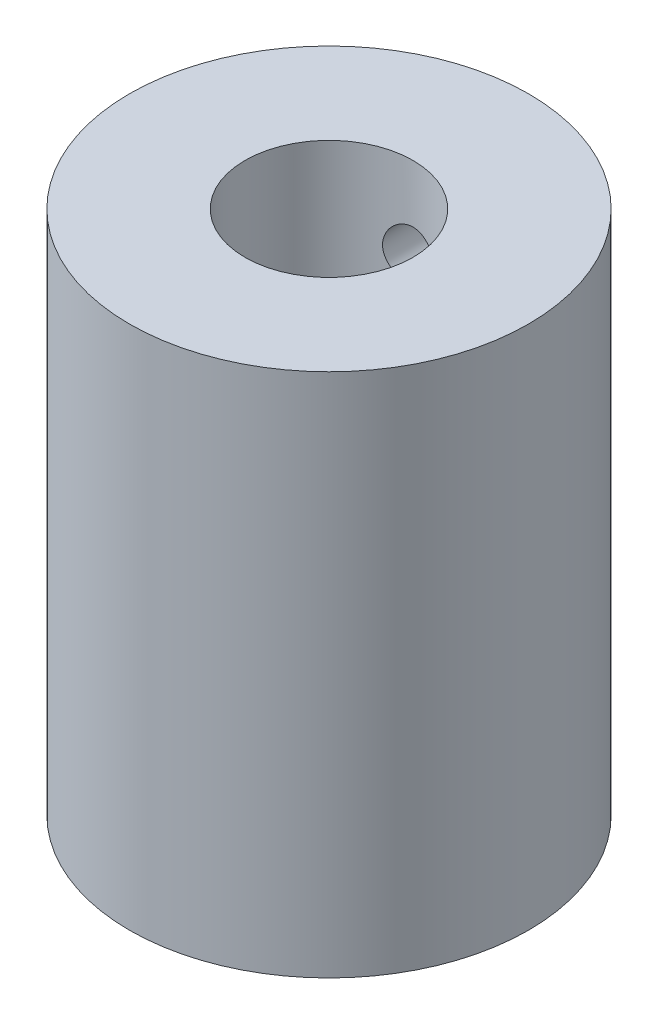
SolidWorks part; units mm, degrees
ref_plane "Front Plane" through (0, 0, 0) normal (0, 0, 1) x (1, 0, 0)
ref_plane "Top Plane" through (0, 0, 0) normal (0, 1, 0) x (1, 0, 0)
ref_plane "Right Plane" through (0, 0, 0) normal (1, 0, 0) x (0, 0, -1)
sketch "Sketch1" plane through (0, 0, 0) normal (0, 1, 0) x (1, 0, 0)
  circle A0 centre (0, 0) radius 9.5
  dimension "D1" = 19
extrude "Boss-Extrude1" add sketch "Sketch1" along normal blind 25
sketch "Sketch2" plane through (0, 25, 0) normal (0, 1, 0) x (1, 0, 0)
  line L0 (0, 9.5) -> (0, -9.5) construction
  circle A0 centre (0, 0) radius 9.5 construction
  circle A1 centre (0, 0) radius 4
  dimension "D1" = 8
extrude "Cut-Extrude1" cut sketch "Sketch2" against normal blind 12.5
sketch "Sketch3" plane through (0, 0, 0) normal (0, -1, 0) x (1, 0, 0)
  line L0 (0, 9.5) -> (0, -9.5) construction
  circle A0 centre (0, 0) radius 9.5 construction
  circle A1 centre (0, 0) radius 2.5
  dimension "D1" = 5
extrude "Cut-Extrude2" cut sketch "Sketch3" against normal blind 12.5
sketch "Sketch4" plane through (0, 0, 0) normal (0, 0, 1) x (1, 0, 0)
  line L0 (0, 25) -> (0, 0) construction
  line L1 (4, 25) -> (-4, 25) construction
  line L2 (-9.5, 0) -> (9.5, 0) construction
  line L3 (-9.5, 12.5) -> (9.5, 12.5) construction
  line L4 (-9.5, 25) -> (-9.5, 0) construction
  line L5 (9.5, 0) -> (9.5, 25) construction
  circle A0 centre (0, 4) radius 1.25
  circle A1 centre (0, 21) radius 1.25
  point P17 (9.5, 12.5)
  dimension "D1" = 2.5
  dimension "D2" = 4
extrude "Cut-Extrude3" cut sketch "Sketch4" against normal blind 12.5
